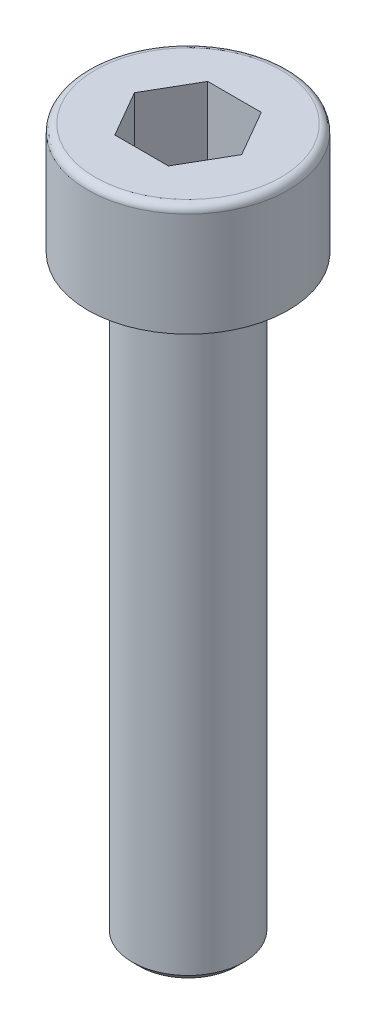
SolidWorks part; units mm, degrees
material "1023 Carbon Steel Sheet (SS)"
ref_plane "Front" through (0, 0, 0) normal (0, 0, 1) x (1, 0, 0)
ref_plane "Top" through (0, 0, 0) normal (0, 1, 0) x (1, 0, 0)
ref_plane "Right" through (0, 0, 0) normal (1, 0, 0) x (0, 0, -1)
sketch "Sketch1" plane through (0, 0, 0) normal (1, 0, 0) x (0, 0, -1)
  line L0 (0, 11.8275) -> (0, 0) construction
  line L1 (0, 0) -> (14.4314, 0) construction
  line L2 (0, 3) -> (0, -16)
  line L3 (0, -16) -> (1.3, -16)
  line L4 (1.3, -16) -> (1.5, -15.8)
  line L5 (1.5, -15.8) -> (1.5, -0.2)
  line L6 (1.7, 0) -> (2.7, 0)
  line L7 (2.7, 0) -> (2.7, 2.8)
  line L8 (2.5, 3) -> (0, 3)
  arc A0 (1.5, -0.2) -> (1.7, 0) centre (1.7, -0.2) cw
  arc A1 (2.7, 2.8) -> (2.5, 3) centre (2.5, 2.8) ccw
  dimension "D6" = 0.2
  dimension "D1" = 16
  dimension "D2" = 5.4
  dimension "D3" = 3
  dimension "D4" = 45
  dimension "D5" = 0.2
  dimension "D7" = 3
revolve "Revolve1" add sketch "Sketch1" angle 360 about L0
cosmetic thread "Cosmetic Thread1"
sketch "Sketch2" plane through (0, 3, 0) normal (0, 1, 0) x (1, 0, 0)
  line L1 (0.7217, 1.25) -> (-0.7217, 1.25)
  line L2 (-0.7217, 1.25) -> (-1.4434, 0)
  line L3 (-1.4434, 0) -> (-0.7217, -1.25)
  line L4 (-0.7217, -1.25) -> (0.7217, -1.25)
  line L5 (0.7217, -1.25) -> (1.4434, 0)
  line L6 (1.4434, 0) -> (0.7217, 1.25)
  circle A0 centre (0, 0) radius 1.25 construction
  dimension "D1" = 2.5
extrude "Cut-Extrude1" cut sketch "Sketch2" against normal blind 2
equation "\"Screw Length\"= 16"
equation "\"D1@Sketch1\"=\"Screw Length\""
